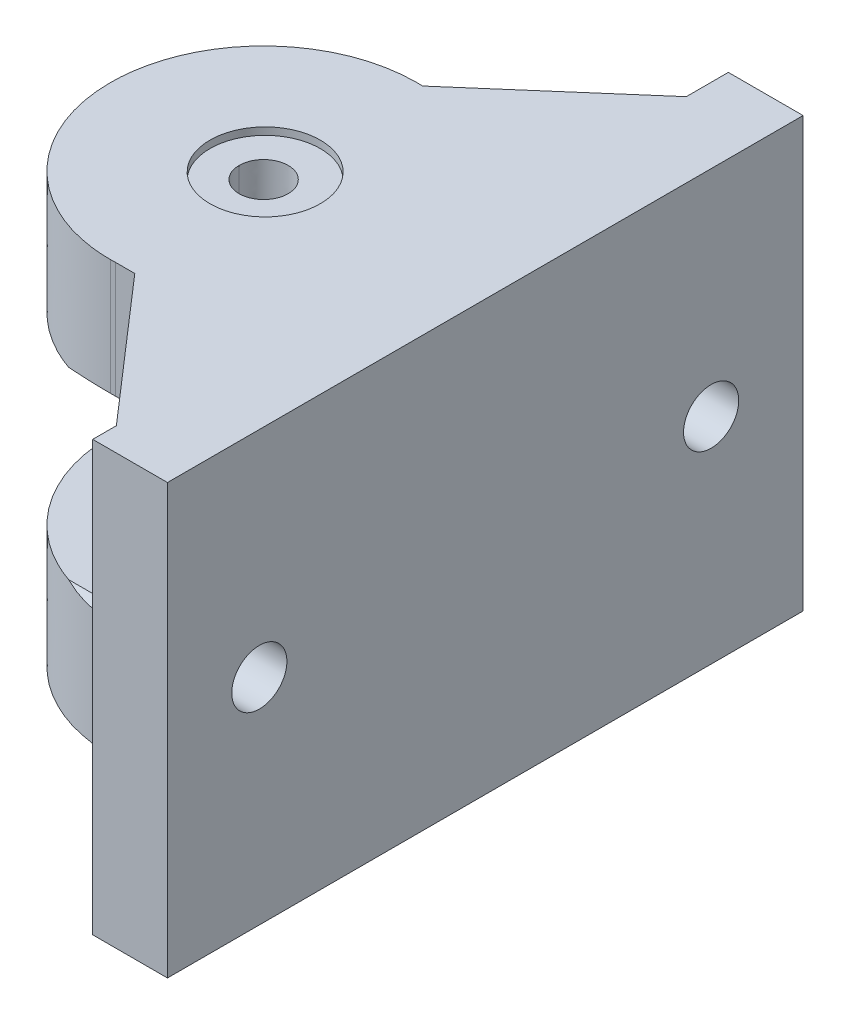
SolidWorks part; units mm, degrees
ref_plane "Front Plane" through (0, 0, 0) normal (0, 0, 1) x (1, 0, 0)
ref_plane "Top Plane" through (0, 0, 0) normal (0, 1, 0) x (1, 0, 0)
ref_plane "Right Plane" through (0, 0, 0) normal (1, 0, 0) x (0, 0, -1)
sketch "Sketch1" plane through (0, 0, 0) normal (0, 1, 0) x (1, 0, 0)
  line L0 (30.578, 38.4121) -> (30.578, 51.8446)
  line L1 (30.578, 51.8446) -> (24.4802, 51.8446)
  line L2 (24.4802, 51.8446) -> (24.4802, 38.4121)
  line L3 (24.4802, 38.4121) -> (12.8952, 38.4121)
  line L4 (12.8952, 13.4324) -> (24.4802, 13.4324)
  line L5 (24.4802, 13.4324) -> (24.4802, 0)
  line L6 (24.4802, 0) -> (30.578, 0)
  line L7 (30.578, 0) -> (30.578, 13.4324)
  line L8 (30.578, 13.4324) -> (30.578, 38.4121)
  spline S0 degree 3 poles (12.8952, 38.4121) (12.7636, 38.4163) (12.6325, 38.4221) (12.4998, 38.4221) knots 4 4 4 4 5 5 5 5
  spline S1 degree 3 poles (12.4998, 38.4221) (5.5962, 38.4221) (0, 32.8259) (0, 25.9223) knots 5 5 5 5 6 6 6 6
  spline S2 degree 3 poles (0, 25.9223) (0, 19.0186) (5.5962, 13.4224) (12.4998, 13.4224) knots 6 6 6 6 7 7 7 7
  spline S3 degree 3 poles (12.4998, 13.4224) (12.6325, 13.4224) (12.7636, 13.4283) (12.8952, 13.4324) knots 7 7 7 7 8 8 8 8
  spline S4 degree 3 poles (10.5, 25.9226) (10.5, 27.0271) (11.3953, 27.9225) (12.5, 27.9225) (13.6045, 27.9225) (14.4999, 27.0271) (14.4999, 25.9226) knots 2 2 2 2 3 3 3 4 4 4 4
  spline S5 degree 3 poles (14.4999, 25.9226) (14.4999, 24.8178) (13.6045, 23.9224) (12.5, 23.9224) (11.3953, 23.9224) (10.5, 24.8178) (10.5, 25.9226) knots 0 0 0 0 1 1 1 2 2 2 2
extrude "Boss-Extrude1" add sketch "Sketch1" along normal blind 35
sketch "Sketch2" plane through (0, 0, -13.4324) normal (0, 0, 1) x (1, 0, 0)
  line L0 (24.4802, 35) -> (24.4802, 0) construction
  line L1 (24.4802, 35) -> (0, 35)
  line L2 (24.4802, 35) -> (24.4802, 25)
  line L3 (24.4802, 25) -> (0, 25)
  line L4 (0, 35) -> (0, 25)
  line L5 (0, 0) -> (24.4802, 0)
  line L6 (0, 0) -> (0, 10)
  line L7 (0, 10) -> (24.4802, 10)
  line L8 (24.4802, 0) -> (24.4802, 10)
  line L11 (0, 25) -> (0, 10)
  line L13 (24.4802, 25) -> (24.4802, 10)
  line M4 (24.4802, 0) -> (24.4802, 35)
  line M6 (12.8952, 35) -> (12.8952, 0)
  dimension "D1" = 10
  dimension "D2" = 10
extrude "Cut-Extrude1" cut sketch "Sketch2" along normal blind 35 and the other way blind 35 contours L3 L11 L7 M6 | L7 L3 M6 M4
chamfer "Chamfer1" distance 10 angle 49 4 edges at (24.4802, 30, -13.4324) (24.4802, 5, -13.4324) (24.4802, 5, -38.4121) (24.4802, 30, -38.4121)
sketch "Sketch3" plane through (24.4802, 0, 0) normal (-1, 0, 0) x (0, 0, 1)
  line L0 (-51.8446, 35) -> (-51.8446, 0) construction
  line L1 (-51.8446, 17.5) -> (-44.3446, 17.5)
  line L2 (0, 17.5) -> (-7.4932, 17.5)
  circle A0 centre (-44.3446, 17.5) radius 2.25
  circle A1 centre (-7.4932, 17.5) radius 2.25
  dimension "D1" = 7.5
extrude "Cut-Extrude2" cut sketch "Sketch3" against normal through all
chamfer "Chamfer2" distance 1.5 angle 49 2 edges at (24.4802, 17.5, -5.2432) (24.4802, 17.5, -42.0946)
sketch "Sketch5" plane through (0, 35, 0) normal (0, 1, 0) x (1, 0, 0)
  circle A0 centre (12.6209, 25.9226) radius 4.5
extrude "Cut-Extrude3" cut sketch "Sketch5" against normal blind 0.6
sketch "Sketch8" plane through (0, 0, 0) normal (0, -1, 0) x (1, 0, 0)
  line L1 (15.1954, -28.4733) -> (16.0846, -24.771)
  line L2 (16.0846, -24.771) -> (13.3229, -22.1497)
  line L3 (13.3229, -22.1497) -> (9.672, -23.2308)
  line L4 (9.672, -23.2308) -> (8.7828, -26.9331)
  line L5 (8.7828, -26.9331) -> (11.5445, -29.5544)
  line L6 (11.5445, -29.5544) -> (15.1954, -28.4733)
  circle A0 centre (12.4337, -25.8521) radius 3.2975 construction
extrude "Cut-Extrude4" cut sketch "Sketch8" against normal blind 1.5
sketch "Sketch9" plane through (24.4802, 0, 0) normal (-1, 0, 0) x (0, 0, 1)
  circle A0 centre (-7.4932, 17.5) radius 10
  circle A1 centre (-44.3446, 17.5) radius 10
extrude "Cut-Extrude5" cut sketch "Sketch9" along normal blind 35
